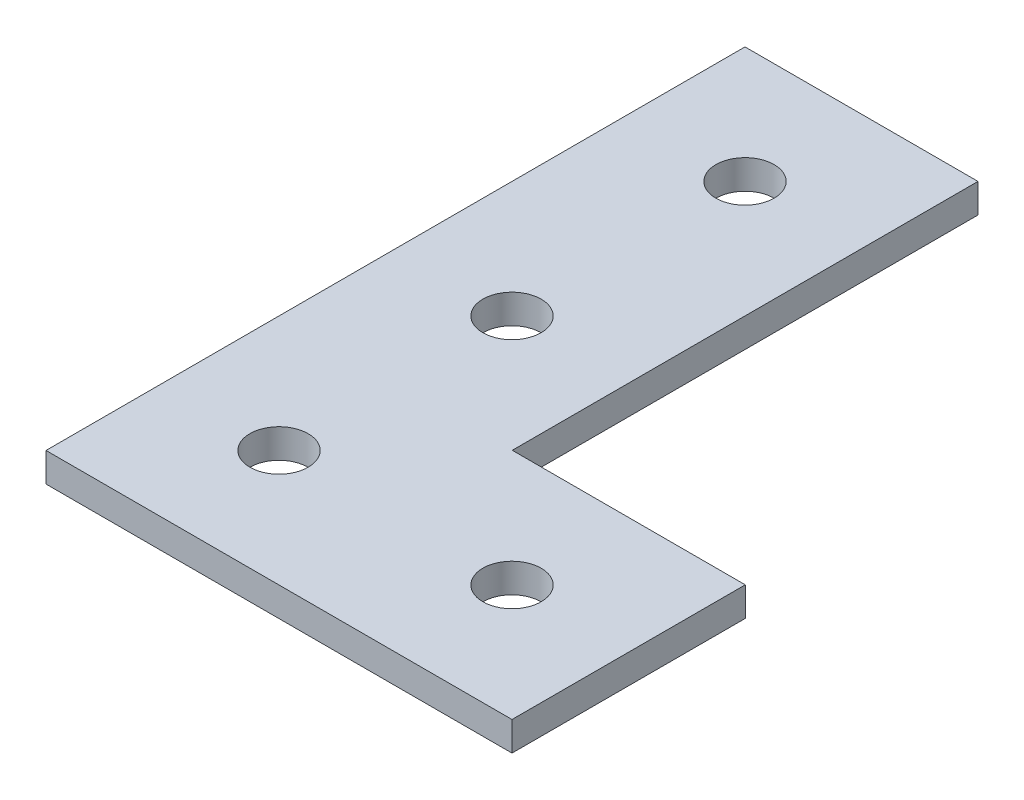
SolidWorks part; units mm, degrees
ref_plane "Front Plane" through (0, 0, 0) normal (0, 0, 1) x (1, 0, 0)
ref_plane "Top Plane" through (0, 0, 0) normal (0, 1, 0) x (1, 0, 0)
ref_plane "Right Plane" through (0, 0, 0) normal (1, 0, 0) x (0, 0, -1)
sketch "Sketch1" plane through (0, 0, 0) normal (0, 1, 0) x (1, 0, 0)
  line L0 (0, 0) -> (0, 76.2)
  line L1 (0, 76.2) -> (25.4, 76.2)
  line L2 (25.4, 76.2) -> (25.4, 25.4296)
  line L3 (25.4, 25.4296) -> (50.8, 25.4296)
  line L4 (50.8, 25.4296) -> (50.8, 0)
  line L5 (50.8, 0) -> (0, 0)
  dimension "D1" = 76.2
  dimension "D2" = 50.8
  dimension "D3" = 25.4
extrude "Boss-Extrude1" add sketch "Sketch1" along normal blind 3.175
sketch "Sketch2" plane through (0, 3.175, 0) normal (0, 1, 0) x (1, 0, 0)
  line L2 (12.7, 9.525) -> (12.7, 13.0441)
  circle A0 centre (12.7, 12.7) radius 3.175
  dimension "D3" = 6.35
extrude "Cut-Extrude1" cut sketch "Sketch2" against normal blind 3.175 contours A0
pattern_linear "LPattern1" count 3 spacing 25.4 along (0, 0, -1) of "Cut-Extrude1"
pattern_linear "LPattern2" count 2 spacing 25.4 along (1, 0, 0) of "Cut-Extrude1"
